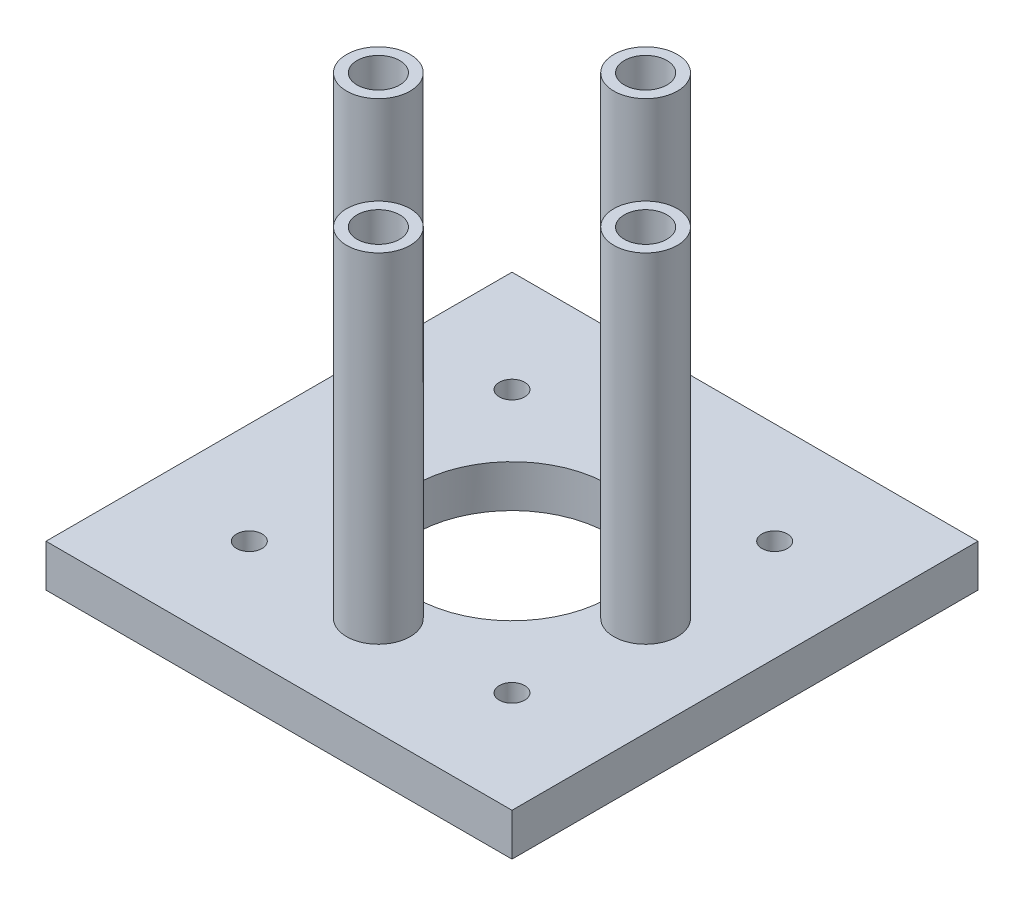
SolidWorks part; units mm, degrees
ref_plane "Front Plane" through (0, 0, 0) normal (0, 0, 1) x (1, 0, 0)
ref_plane "Top Plane" through (0, 0, 0) normal (0, 1, 0) x (1, 0, 0)
ref_plane "Right Plane" through (0, 0, 0) normal (1, 0, 0) x (0, 0, -1)
sketch "Sketch1" plane through (0, 0, 0) normal (0, 1, 0) x (1, 0, 0)
  line L1 (-27.5, -27.5) -> (27.5, -27.5)
  line L2 (-27.5, -27.5) -> (-27.5, 27.5)
  line L3 (-27.5, 27.5) -> (27.5, 27.5)
  line L4 (27.5, -27.5) -> (27.5, 27.5)
  line L5 (-27.5, -27.5) -> (27.5, 27.5) construction
  line L6 (-27.5, 27.5) -> (27.5, -27.5) construction
  circle A0 centre (-15.5, 15.5) radius 1.5
  circle A1 centre (-15.5, -15.5) radius 1.5
  circle A2 centre (15.5, -15.5) radius 1.5
  circle A3 centre (15.5, 15.5) radius 1.5
  point P0 (0, 0)
  dimension "D1" = 55
  dimension "D2" = 55
extrude "Boss-Extrude1" add sketch "Sketch1" along normal blind 5
sketch "Sketch2" plane through (0, 5, 0) normal (0, 1, 0) x (1, 0, 0)
  line L0 (-27.5, 27.5) -> (27.5, -27.5) construction
  line L1 (-27.5, -27.5) -> (27.5, 27.5) construction
  line L2 (-27.5, 0) -> (27.5, 0) construction
  line L3 (0, -27.5) -> (0, 27.5) construction
  line L4 (-27.5, -27.5) -> (27.5, -27.5) construction
  line L5 (-27.5, 27.5) -> (-27.5, -27.5) construction
  line L6 (27.5, -27.5) -> (27.5, 27.5) construction
  line L7 (27.5, 27.5) -> (-27.5, 27.5) construction
  circle A0 centre (-15.77, 0) radius 3.75
  circle A1 centre (-15.77, 0) radius 2.5118
  circle A13 centre (15.77, 0) radius 2.5118
  circle A14 centre (15.77, 0) radius 3.75
  circle A15 centre (0, -15.77) radius 3.75
  circle A16 centre (0, -15.77) radius 2.5118
  circle A17 centre (0, 15.77) radius 2.5118
  circle A18 centre (0, 15.77) radius 3.75
  dimension "D3" = 7.5
extrude "Boss-Extrude2" add sketch "Sketch2" along normal blind 40
sketch "Sketch3" plane through (0, 5, 0) normal (0, 1, 0) x (1, 0, 0)
  circle A0 centre (0, 0) radius 11.5
extrude "Cut-Extrude1" cut sketch "Sketch3" against normal blind 15
